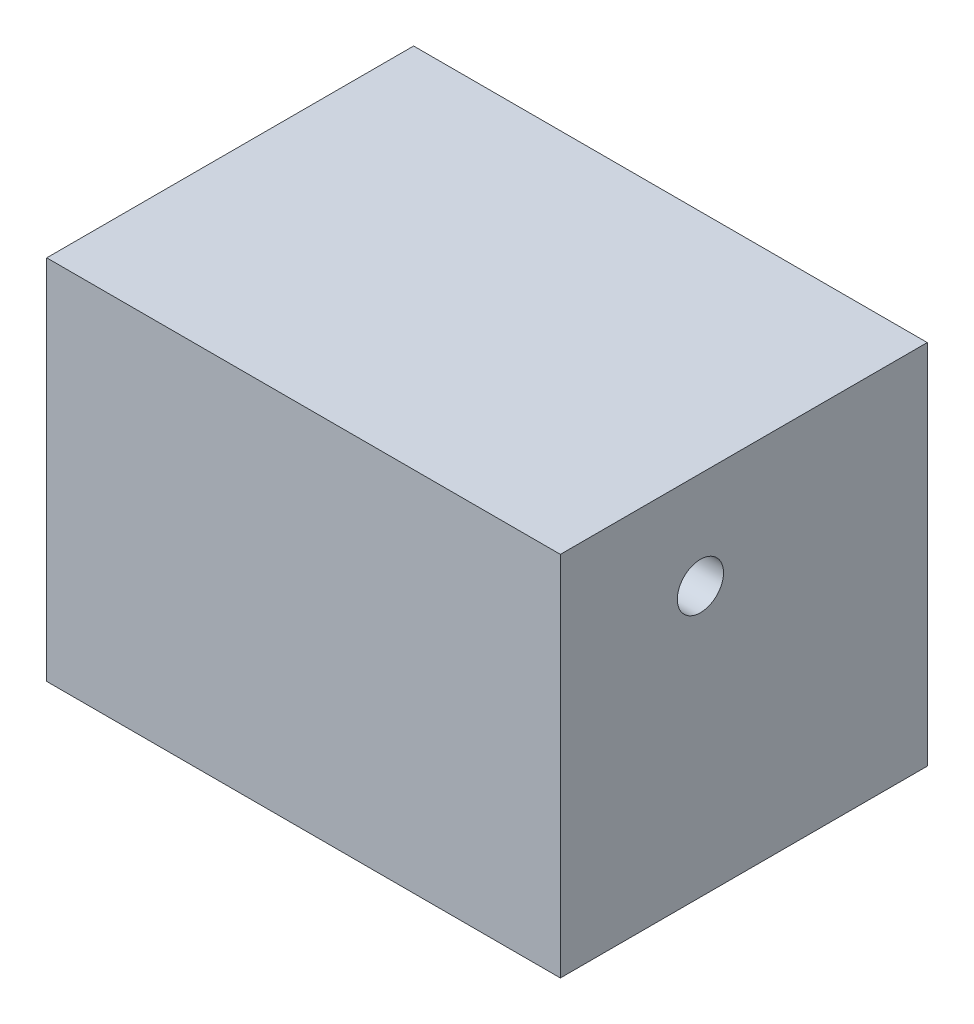
SolidWorks part; units mm, degrees
ref_plane "Front Plane" through (0, 0, 0) normal (0, 0, 1) x (1, 0, 0)
ref_plane "Top Plane" through (0, 0, 0) normal (0, 1, 0) x (1, 0, 0)
ref_plane "Right Plane" through (0, 0, 0) normal (1, 0, 0) x (0, 0, -1)
sketch "Sketch1" plane through (0, 0, 0) normal (0, 0, 1) x (1, 0, 0)
  line L1 (-42.4084, 21.3351) -> (27.5916, 21.3351)
  line L2 (-42.4084, 21.3351) -> (-42.4084, -28.6649)
  line L3 (-42.4084, -28.6649) -> (27.5916, -28.6649)
  line L4 (27.5916, 21.3351) -> (27.5916, -28.6649)
  dimension "D1" = 50
  dimension "D2" = 70
extrude "Boss-Extrude1" add sketch "Sketch1" along normal blind 50
sketch "Sketch2" plane through (0, 0, 0) normal (0, 0, -1) x (-1, 0, 0)
  line L0 (-27.5916, -28.6649) -> (-27.5916, 21.3351) construction
  line L1 (-22.5916, 16.3351) -> (37.4084, 16.3351)
  line L2 (-22.5916, 16.3351) -> (-22.5916, -23.6649)
  line L3 (-22.5916, -23.6649) -> (37.4084, -23.6649)
  line L4 (37.4084, 16.3351) -> (37.4084, -23.6649)
  line L5 (-27.5916, 21.3351) -> (42.4084, 21.3351) construction
  line L6 (42.4084, 21.3351) -> (42.4084, -28.6649) construction
  line L7 (42.4084, -28.6649) -> (-27.5916, -28.6649) construction
  dimension "D1" = 5
  dimension "D2" = 5
  dimension "D3" = 5
  dimension "D4" = 5
extrude "Cut-Extrude1" cut sketch "Sketch2" against normal blind 40 from offset 5 offset against normal yes
sketch "Sketch3" plane through (0, -23.6649, 0) normal (0, 1, 0) x (1, 0, 0)
  circle A0 centre (11.4363, -25.2545) radius 3
extrude "Cut-Extrude2" cut sketch "Sketch3" against normal up to next
sketch "Sketch4" plane through (27.5916, 0, 0) normal (1, 0, 0) x (0, 0, -1)
  circle A0 centre (-30.9133, 8.0566) radius 3.1497
extrude "Cut-Extrude3" cut sketch "Sketch4" against normal up to next
sketch "Sketch5" plane through (-42.4084, 0, 0) normal (-1, 0, 0) x (0, 0, 1)
  circle A0 centre (23.9998, 3.3605) radius 4.1445
extrude "Cut-Extrude4" cut sketch "Sketch5" against normal up to next
